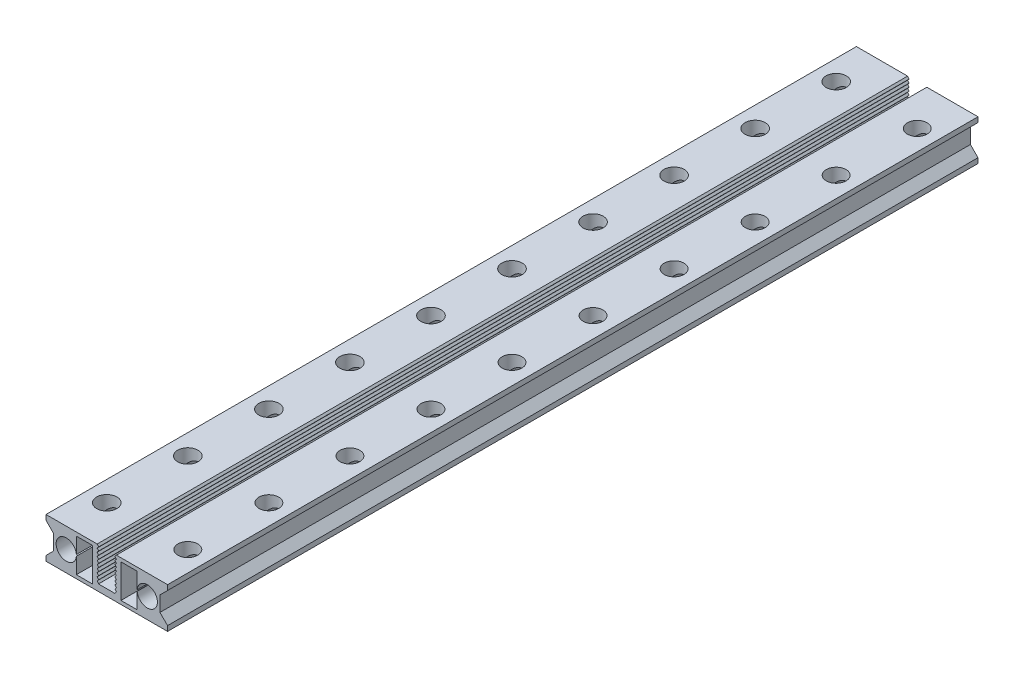
SolidWorks part; units mm, degrees
ref_plane "前视基准面" through (0, 0, 0) normal (0, 0, 1) x (1, 0, 0)
ref_plane "上视基准面" through (0, 0, 0) normal (0, 1, 0) x (1, 0, 0)
ref_plane "右视基准面" through (0, 0, 0) normal (1, 0, 0) x (0, 0, -1)
sketch "草图1" plane through (0, 0, 0) normal (0, 0, 1) x (1, 0, 0)
  line L0 (-12, 8) -> (-12, 7)
  line L1 (-12, 7) -> (-10.5, 5.5)
  line L2 (-10.5, 5.5) -> (-10.5, 2.5)
  line L3 (-10.5, 2.5) -> (-12, 1)
  line L4 (-12, 1) -> (-12, 0)
  line L5 (-12, 0) -> (12, 0)
  line L6 (12, 0) -> (12, 1)
  line L7 (12, 1) -> (10.5, 2.5)
  line L8 (10.5, 2.5) -> (10.5, 5.5)
  line L9 (10.5, 5.5) -> (12, 7)
  line L10 (12, 7) -> (12, 8)
  line L11 (12, 8) -> (1.9, 8)
  line L12 (0, 0) -> (0, 8) construction
  line L13 (-8, 4) -> (8, 4) construction
  line L14 (-1.9, 8) -> (-1.9, 1.3)
  line L15 (-6.005, 7.3) -> (-2.8, 7.3)
  line L16 (-6.005, 7.3) -> (-6.005, 4.1413)
  line L17 (-6.005, 0.7) -> (-2.8, 0.7)
  line L18 (-2.8, 7.3) -> (-2.8, 0.7)
  line L19 (-1.9, 1.3) -> (1.9, 1.3)
  line L20 (1.9, 1.3) -> (1.9, 8)
  line L21 (-1.9, 8) -> (-12, 8)
  line L22 (-6.005, 3.8587) -> (-6.005, 0.7)
  line L23 (2.8, 7.3) -> (6.005, 7.3)
  line L24 (2.8, 7.3) -> (2.8, 0.7)
  line L25 (2.8, 0.7) -> (6.005, 0.7)
  line L26 (6.005, 7.3) -> (6.005, 4.1413)
  line L27 (6.005, 3.8587) -> (6.005, 0.7)
  arc A0 (-6.005, 4.1413) -> (-6, 4) centre (-8, 4) ccw
  arc A1 (6.005, 3.8587) -> (6.005, 4.1413) centre (8, 4) ccw
  point P19 (10.5, 4)
  point P24 (-2.8, 4)
  point P27 (0, 1.3)
  dimension "D4" = 4
  dimension "D1" = 24
  dimension "D2" = 8
  dimension "D3" = 45
  dimension "D5" = 16
  dimension "D6" = 8
  dimension "D7" = 3
  dimension "D8" = 1
  dimension "D9" = 4
  dimension "D10" = 3.8
  dimension "D11" = 1.3
  dimension "D12" = 5.6
  dimension "D13" = 2.8
  dimension "D14" = 12.01
  dimension "D15" = 0.7
extrude "凸台-拉伸2" add sketch "草图1" along normal blind 160 contours L14 L21 L0 L1 L2 L3 L4 L5 L6 L7 L8 L9 L10 L11 L20 L19 A1 L27 L25 L24 L23 L26 A0 L16 L15 L18 L17 L22
sketch "草图3" plane through (0, 0, 160) normal (0, 0, 1) x (1, 0, 0)
  line L0 (-1.9, 8) -> (-1.6, 7.65)
  line L1 (-1.6, 7.65) -> (-1.9, 7.3)
  line L2 (-1.9, 8) -> (-1.9, 1.3) construction
  line L3 (-1.9, 7.3) -> (-1.9, 8)
  point P7 (-1.9, 7.65)
  dimension "D1" = 0.7
  dimension "D2" = 0.3
extrude "凸台-拉伸3" add sketch "草图3" against normal up to surface (160 mm away) up to face at (5.6025, 4, 0)
pattern_linear "阵列(线性)1" count 10 spacing 0.7 along (0, -1, 0) of "凸台-拉伸3"
mirror "镜向1" about plane through (0, 0, 0) normal (1, 0, 0) of "阵列(线性)1", "凸台-拉伸3"
sketch "草图4" plane through (0, 8, 0) normal (0, 1, 0) x (1, 0, 0)
  line L1 (12, 0) -> (1.9, 0) construction
  circle A0 centre (-8, -8) radius 2
  circle A1 centre (8, -8) radius 1.95
  dimension "D1" = 16
  dimension "D4" = 3.9
  dimension "D5" = 4
  dimension "D2" = 8
  dimension "D3" = 8
extrude "切除-拉伸1" cut sketch "草图4" against normal through all
pattern_linear "阵列(线性)2" count 10 spacing 16 along (0, 0, 1) of "切除-拉伸1"
equation "\"D13@草图1\"=\"D12@草图1\"/2"
